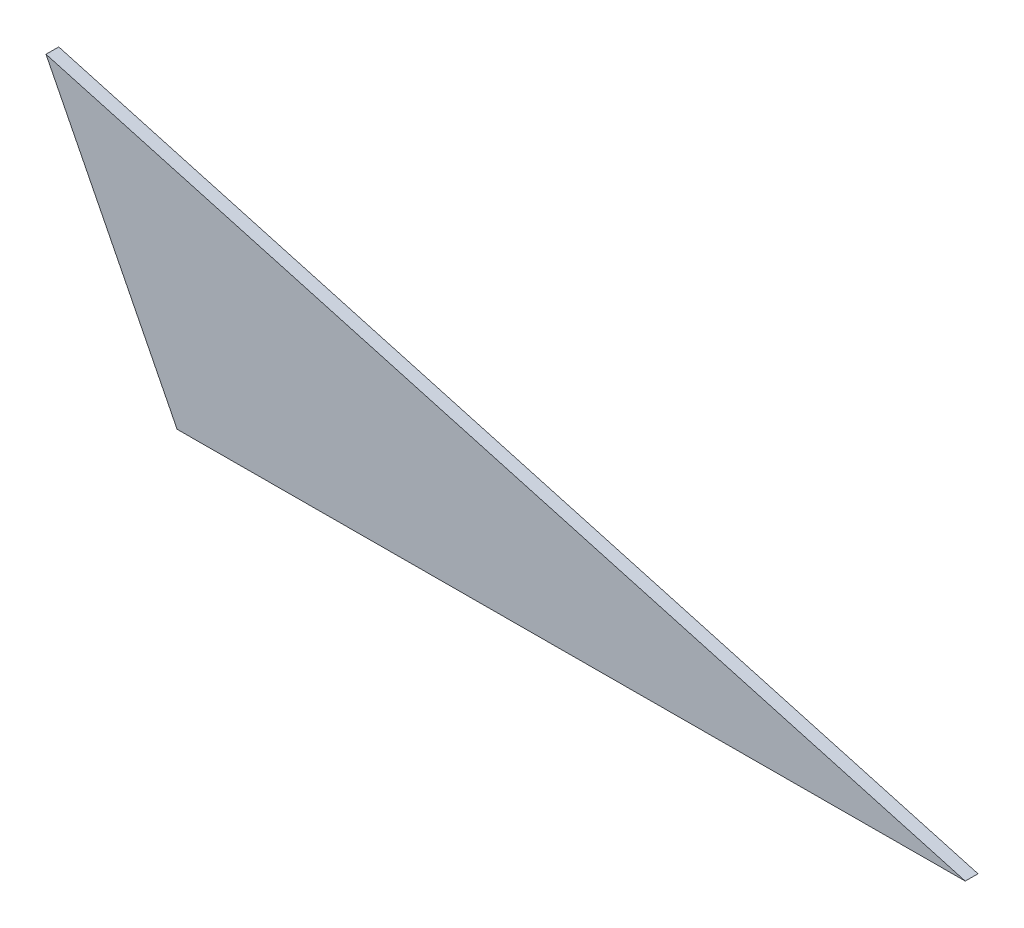
SolidWorks part; units mm, degrees
ref_plane "Front Plane" through (0, 0, 0) normal (0, 0, 1) x (1, 0, 0)
ref_plane "Top Plane" through (0, 0, 0) normal (0, 1, 0) x (1, 0, 0)
ref_plane "Right Plane" through (0, 0, 0) normal (1, 0, 0) x (0, 0, -1)
sketch "Sketch1" plane through (0, 0, 0) normal (0, 0, 1) x (1, 0, 0)
  line L0 (-473.5004, 133.9996) -> (793.1429, -219.3272) construction
  line L1 (-473.5004, 133.9996) -> (-292.8502, -223.1985) construction
  line L2 (-292.8502, -223.1985) -> (793.1429, -219.3272) construction
  line L3 (-435.1812, 102.5471) -> (648.8529, -199.8414)
  line L4 (-280.575, -203.1546) -> (648.8529, -199.8414)
  line L5 (-435.1812, 102.5471) -> (-280.575, -203.1546)
  dimension "D1" = 400.2812
  dimension "D2" = 1315
  dimension "D3" = 1086
  dimension "D4" = 20
extrude "Boss-Extrude1" add sketch "Sketch1" along normal blind 15
